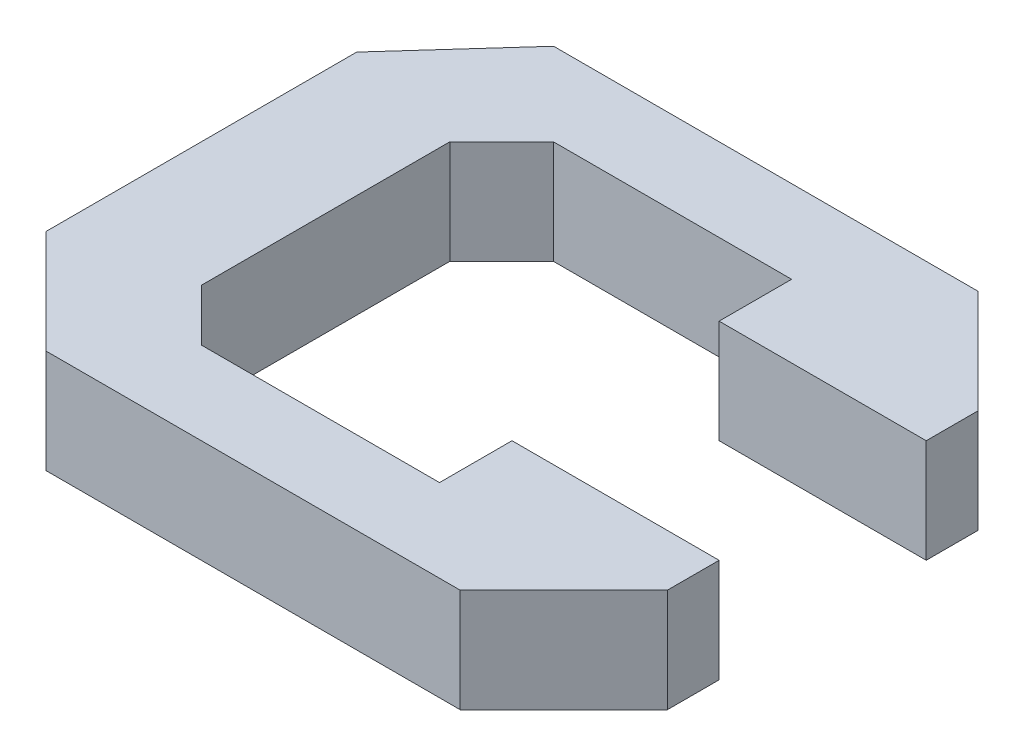
SolidWorks part; units mm, degrees
ref_plane "Front Plane" through (0, 0, 0) normal (0, 0, 1) x (1, 0, 0)
ref_plane "Top Plane" through (0, 0, 0) normal (0, 1, 0) x (1, 0, 0)
ref_plane "Right Plane" through (0, 0, 0) normal (1, 0, 0) x (0, 0, -1)
sketch "Sketch1" plane through (0, 0, 0) normal (0, 1, 0) x (1, 0, 0)
  line L1 (0, 0) -> (-38.1, 0)
  line L2 (0, 0) -> (0, 31.75)
  line L3 (0, 31.75) -> (-38.1, 31.75)
  line L4 (-38.1, 0) -> (-38.1, 31.75)
  dimension "D1" = 31.75
  dimension "D2" = 38.1
extrude "Boss-Extrude1" add sketch "Sketch1" along normal blind 6.35
sketch "Sketch2" plane through (0, 6.35, 0) normal (0, 1, 0) x (1, 0, 0)
  line L0 (0, 0) -> (0, 31.75) construction
  line L1 (-30.48, 26.67) -> (-12.7, 26.67)
  line L2 (-30.48, 26.67) -> (-30.48, 5.08)
  line L3 (-30.48, 5.08) -> (-12.7, 5.08)
  line L4 (-12.7, 26.67) -> (-12.7, 5.08)
  line L5 (-12.7, 22.225) -> (0, 22.225)
  line L6 (-12.7, 22.225) -> (-12.7, 9.525)
  line L7 (-12.7, 9.525) -> (0, 9.525)
  line L8 (0, 22.225) -> (0, 9.525)
  line L9 (-38.1, 31.75) -> (-38.1, 0) construction
  line L10 (-38.1, 0) -> (0, 0) construction
  line L11 (0, 31.75) -> (-38.1, 31.75) construction
  line L12 (-30.48, 8.255) -> (-27.305, 5.08)
  line L13 (-30.48, 23.495) -> (-27.305, 26.67)
  line L14 (-6.35, 0) -> (0, 6.35)
  line L15 (0, 25.4) -> (-6.35, 31.75)
  line L16 (-6.35, 0) -> (0, 0)
  line L17 (0, 0) -> (0, 6.35)
  line L18 (0, 25.4) -> (0, 31.75)
  line L19 (0, 31.75) -> (-6.35, 31.75)
  line L20 (-38.1, 25.4) -> (-32.3716, 31.75)
  line L21 (-38.1, 6.35) -> (-31.75, 0)
  line L22 (-32.3716, 31.75) -> (-38.1, 31.75)
  line L23 (-38.1, 31.75) -> (-38.1, 25.4)
  line L26 (-31.75, 0) -> (-38.1, 0)
  line L27 (-38.1, 0) -> (-38.1, 6.35)
  point P38 (-38.1, 2.3916)
  line M7 (0, 0) -> (0, 31.75)
  dimension "D1" = 7.62
  dimension "D2" = 5.08
  dimension "D3" = 0
  dimension "D4" = 12.7
  dimension "D5" = 9.525
  dimension "D6" = 9.525
  dimension "D7" = 45
  dimension "D8" = 45
  dimension "D9" = 3.175
  dimension "D10" = 3.175
  dimension "D11" = 31.75
  dimension "D12" = 45
  dimension "D13" = 31.75
  dimension "D14" = 45
  dimension "D15" = 6.35
  dimension "D16" = 5.7284
  dimension "D17" = 6.35
  dimension "D18" = 6.35
extrude "Cut-Extrude1" cut sketch "Sketch2" against normal through all contours L13 L2 L12 L3 L4 L1 | L4 L7 L5 M7 | L17 L14 L16 | L19 L15 L18 | L21 L26 L27 | L23 L20 L22
